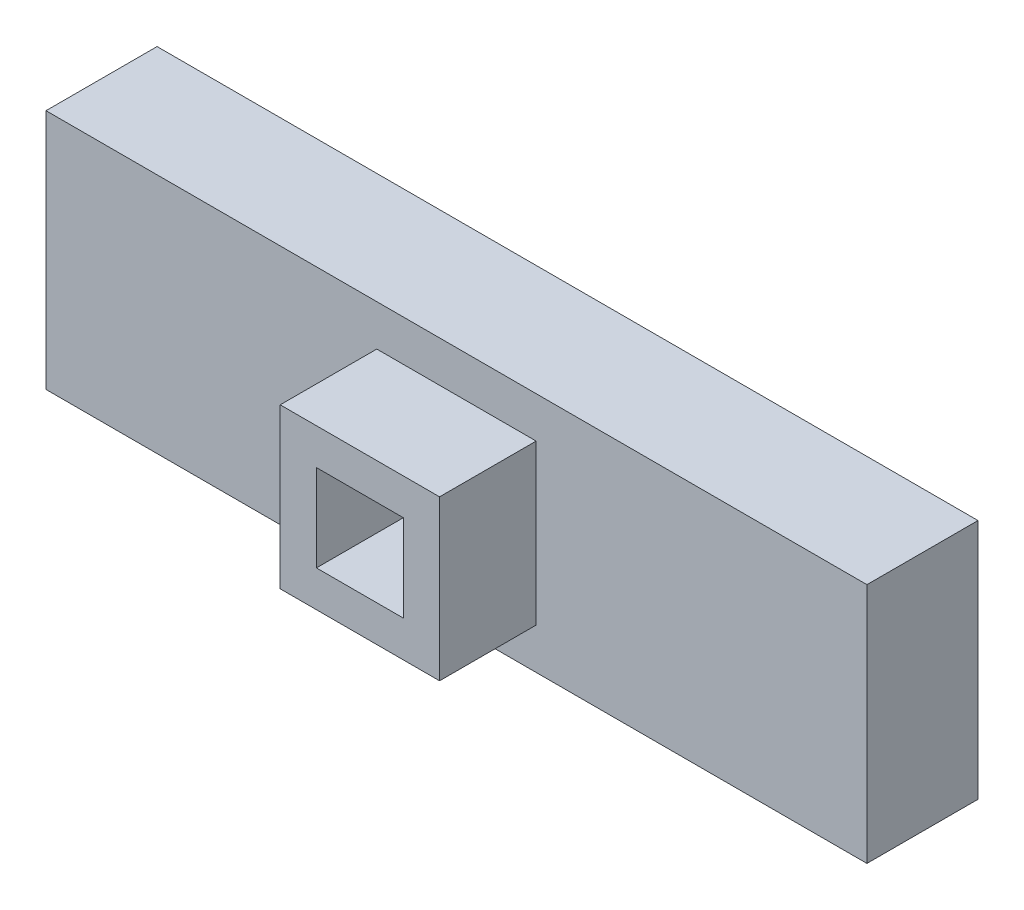
SolidWorks part; units mm, degrees
ref_plane "Alzado" through (0, 0, 0) normal (0, 0, 1) x (1, 0, 0)
ref_plane "Planta" through (0, 0, 0) normal (0, 1, 0) x (1, 0, 0)
ref_plane "Vista lateral" through (0, 0, 0) normal (1, 0, 0) x (0, 0, -1)
sketch "Croquis1" plane through (0, 0, 0) normal (0, 0, 1) x (1, 0, 0)
  line L0 (-45.2172, -4.5564) -> (-11.2172, 5.4436) construction
  line L1 (-45.2172, 5.4436) -> (-11.2172, 5.4436)
  line L2 (-45.2172, 5.4436) -> (-45.2172, -4.5564)
  line L3 (-45.2172, -4.5564) -> (-11.2172, -4.5564)
  line L4 (-11.2172, 5.4436) -> (-11.2172, -4.5564)
  line L5 (-28.2172, 0.4436) -> (-12.2172, 0.4436) construction
  line L6 (-12.2172, 0.4436) -> (-14.2172, 0.4436) construction
  line L7 (-14.2172, 0.4436) -> (-14.2172, 2.4436) construction
  line L8 (-14.2172, 2.4436) -> (-14.2172, -1.5564) construction
  line L9 (-25.841, -2.7741) -> (-25.841, 3.6613) construction
  line L10 (-25.841, 3.6613) -> (-14.2172, 2.4436)
  line L11 (-25.841, -2.7741) -> (-14.2172, -1.5564)
  line L12 (-28.2172, 0.4436) -> (-28.2172, 5.4436) construction
  line L13 (-30.5934, -2.7741) -> (-42.2172, -1.5564)
  line L14 (-30.5934, 3.6613) -> (-42.2172, 2.4436)
  arc A1 (-14.2172, 2.4436) -> (-14.2172, -1.5564) centre (-14.2172, 0.4436) cw
  arc A2 (-42.2172, 2.4436) -> (-42.2172, -1.5564) centre (-42.2172, 0.4436) ccw
  arc A3 (-30.5934, 3.6613) -> (-25.841, 3.6613) centre (-28.2172, 0.4436) cw
  arc A4 (-30.5934, -2.7741) -> (-25.841, -2.7741) centre (-28.2172, 0.4436) ccw
  dimension "D3" = 16
  dimension "D1" = 34
  dimension "D2" = 10
  dimension "D4" = 2
  dimension "D5" = 4
  dimension "D6" = 2
extrude "Saliente-Extruir1" add sketch "Croquis1" along normal blind 3.6
sketch "Croquis2" plane through (0, 0, 3.6) normal (0, 0, 1) x (1, 0, 0)
  line L1 (-45.2172, 5.4436) -> (-11.2172, 5.4436)
  line L2 (-45.2172, 5.4436) -> (-45.2172, -4.5564)
  line L3 (-45.2172, -4.5564) -> (-11.2172, -4.5564)
  line L4 (-11.2172, 5.4436) -> (-11.2172, -4.5564)
extrude "Saliente-Extruir2" add sketch "Croquis2" along normal blind 1
sketch "Croquis3" plane through (0, 0, 4.6) normal (0, 0, 1) x (1, 0, 0)
  line L0 (-45.2172, -4.5564) -> (-11.2172, 5.4436) construction
  line L2 (-31.5172, 3.7436) -> (-24.9172, 3.7436)
  line L3 (-31.5172, 3.7436) -> (-31.5172, -2.8564)
  line L4 (-31.5172, -2.8564) -> (-24.9172, -2.8564)
  line L5 (-24.9172, 3.7436) -> (-24.9172, -2.8564)
  line L6 (-31.5172, 3.7436) -> (-24.9172, -2.8564) construction
  line L7 (-31.5172, -2.8564) -> (-24.9172, 3.7436) construction
  line L8 (-30.0172, -1.3564) -> (-26.4172, -1.3564)
  line L9 (-30.0172, -1.3564) -> (-30.0172, 2.2436)
  line L10 (-30.0172, 2.2436) -> (-26.4172, 2.2436)
  line L11 (-26.4172, -1.3564) -> (-26.4172, 2.2436)
  line L12 (-30.0172, -1.3564) -> (-26.4172, 2.2436) construction
  line L13 (-30.0172, 2.2436) -> (-26.4172, -1.3564) construction
  point P4 (-28.2172, 0.4436)
  point P9 (-28.2172, 0.4436)
  dimension "D1" = 6.6
  dimension "D2" = 6.6
  dimension "D3" = 3.6
extrude "Saliente-Extruir3" add sketch "Croquis3" along normal blind 4
